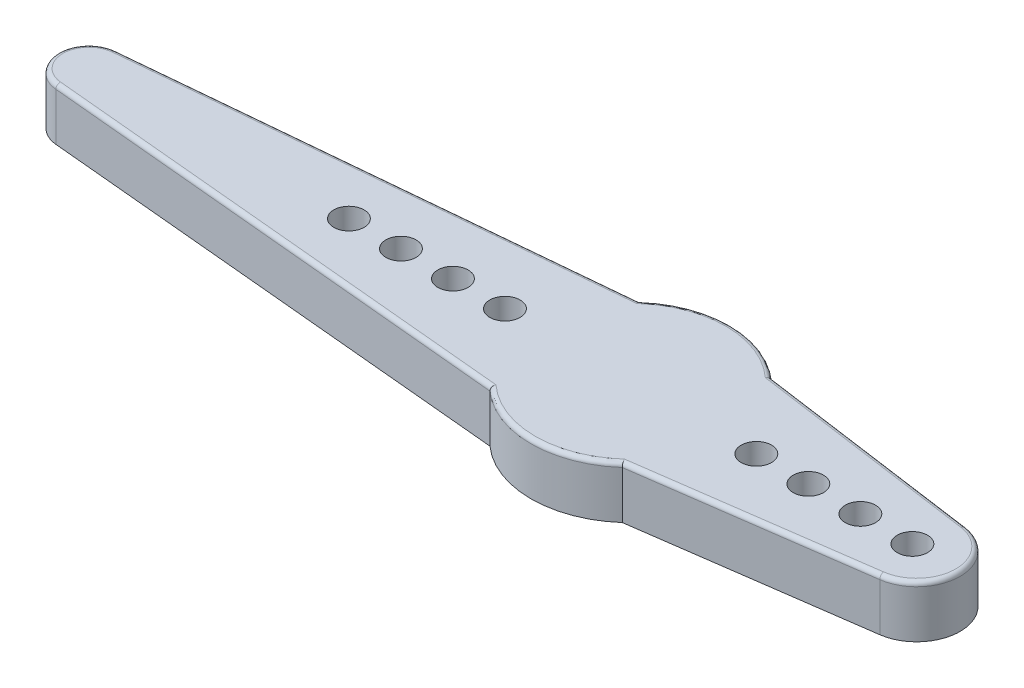
SolidWorks part; units mm, degrees
ref_plane "Front Plane" through (0, 0, 0) normal (0, 0, 1) x (1, 0, 0)
ref_plane "Top Plane" through (0, 0, 0) normal (0, 1, 0) x (1, 0, 0)
ref_plane "Right Plane" through (0, 0, 0) normal (1, 0, 0) x (0, 0, -1)
sketch "Sketch1" plane through (0, 8.7785, 0) normal (0, 1, 0) x (1, 0, 0)
  line L0 (12.0724, -37.2669) -> (39.6665, -34.7094)
  line L1 (12.0724, -40.7519) -> (39.6665, -43.3094)
  line L3 (47.3013, -43.3094) -> (60.3305, -41.4852)
  line L4 (47.3013, -34.7094) -> (60.3305, -36.5335)
  arc A2 (39.6665, -34.7094) -> (47.3013, -34.7094) centre (43.4839, -39.0094) cw
  arc A3 (39.6665, -43.3094) -> (47.3013, -43.3094) centre (43.4839, -39.0094) ccw
  arc A4 (60.3305, -36.5335) -> (60.3305, -41.4852) centre (59.9839, -39.0094) cw
  arc A6 (60.3305, -41.4852) -> (60.3305, -36.5335) centre (59.9839, -39.0094) ccw construction
  circle A7 centre (27.2339, -39.0094) radius 0.875
  circle A8 centre (30.2339, -39.0094) radius 0.875
  circle A9 centre (33.2339, -39.0094) radius 0.875
  circle A10 centre (36.2339, -39.0094) radius 0.875
  circle A11 centre (50.7339, -39.0094) radius 0.875
  circle A12 centre (53.7339, -39.0094) radius 0.875
  circle A13 centre (56.7339, -39.0094) radius 0.875
  circle A14 centre (59.7339, -39.0094) radius 0.875
  circle A15 centre (43.4839, -39.0094) radius 3.5
  arc A16 (12.0724, -40.7519) -> (12.0724, -37.2669) centre (12.2339, -39.0094) cw
  dimension "D2" = 15
  dimension "D3" = 1.75
  dimension "D4" = 7
  dimension "D5" = 1.75
extrude "Boss-Extrude1" add sketch "Sketch1" along normal blind 3
sketch "Sketch2" plane through (0, 11.7785, 0) normal (0, 1, 0) x (1, 0, 0)
  circle A0 centre (43.4839, -39.0094) radius 3.5
  circle A3 centre (43.4839, -39.0094) radius 3.5 construction
extrude "Boss-Extrude2" add sketch "Sketch2" against normal offset from surface (2 mm away) 1 up to face at (39.9133, 8.7785, 39.0094)
fillet "Fillet1" radius 0.25 8 edges at (25.8695, 11.7785, 35.9881) (10.4839, 11.7785, 39.0094) (25.8695, 11.7785, 42.0306) (53.8159, 11.7785, 35.6215) (62.4839, 11.7785, 39.0094) (43.4839, 11.7785, 33.2594) (53.8159, 11.7785, 42.3973) (43.4839, 11.7785, 44.7594)
